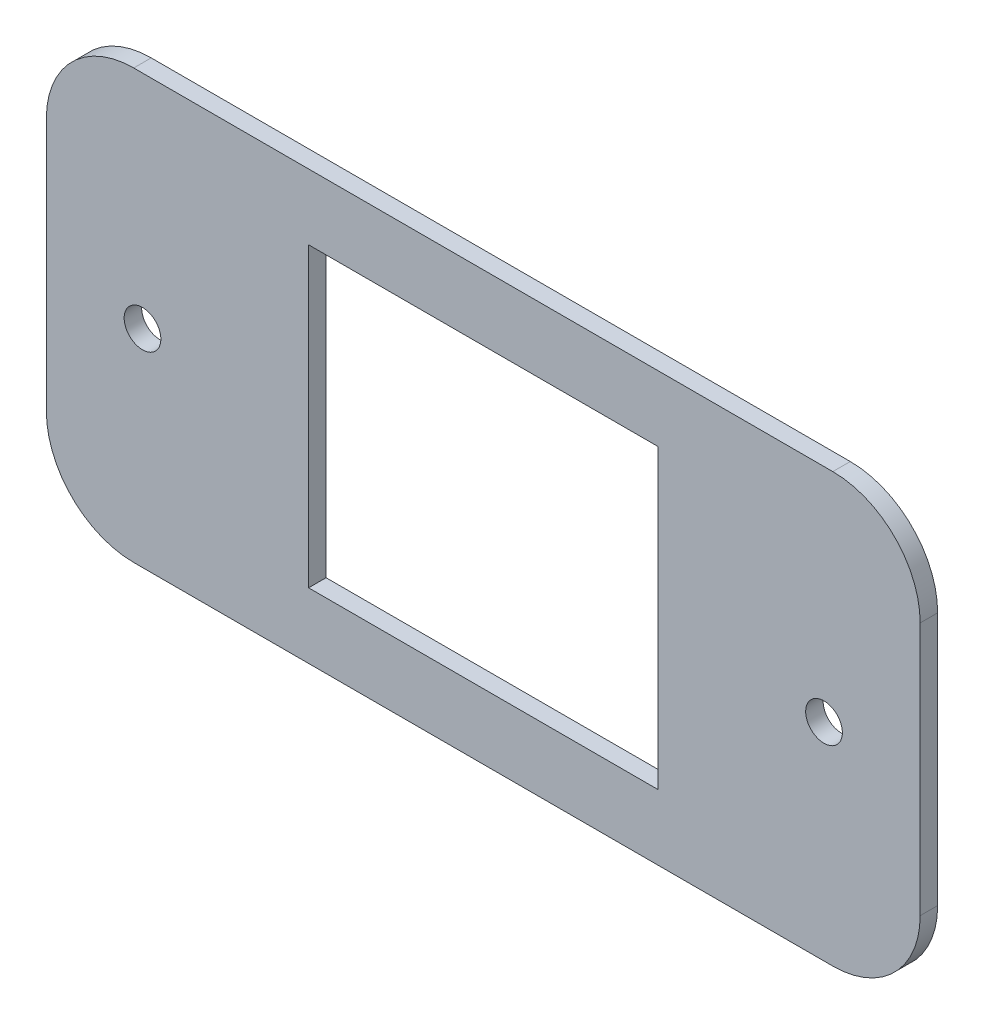
SolidWorks part; units mm, degrees
ref_plane "Front Plane" through (0, 0, 0) normal (0, 0, 1) x (1, 0, 0)
ref_plane "Top Plane" through (0, 0, 0) normal (0, 1, 0) x (1, 0, 0)
ref_plane "Right Plane" through (0, 0, 0) normal (1, 0, 0) x (0, 0, -1)
sketch "Sketch1" plane through (0, 0, 0) normal (0, 0, 1) x (1, 0, 0)
  line L2 (-22.9634, 16.7736) -> (-22.9613, 16.8041)
  line L17 (-22.9613, 16.8041) -> (-23, 16.8041)
  line L19 (13, -13.1959) -> (12.9634, -13.1654) construction
  line L20 (-22.9899, -13.2056) -> (13.0087, -13.2056)
  line L21 (45.0063, -22.7037) -> (-55.0063, -22.7037)
  line L22 (45.0063, -22.7037) -> (45.0063, 26.3119)
  line L23 (45.0063, 26.3119) -> (-55.0063, 26.3119)
  line L24 (-55.0063, -22.7037) -> (-55.0063, 26.3119)
  line L25 (-22.9899, -13.2056) -> (-22.9899, 16.7955)
  line L26 (-22.9899, 16.7955) -> (13.0087, 16.7955)
  line L27 (13.0087, -13.2056) -> (13.0087, 16.7955)
  line L28 (-22.9899, -13.2056) -> (13.0087, 16.7955) construction
  line L29 (-22.9899, 16.7955) -> (13.0087, -13.2056) construction
  line L30 (-22.9634, 16.7736) -> (-23, 16.8041) construction
  line L31 (-24.9899, -15.2056) -> (-24.9899, 18.7955)
  line L32 (-24.9899, 18.7955) -> (15.0087, 18.7955)
  line L33 (15.0087, -15.2056) -> (15.0087, 18.7955)
  line L34 (-24.9899, -15.2056) -> (15.0087, -15.2056)
  circle A0 centre (-44, 0.9817) radius 2.1
  circle A1 centre (34, 0.9817) radius 2.1
  point P0 (0, 0)
  point P1 (-4.9906, 1.7949)
  point P2 (0, 0)
  point P4 (0, 0)
  point P6 (0, 0)
  point P8 (-5, 1.8041)
  point P15 (-5, 1.8041)
  dimension "D1" = 2
extrude "Boss-Extrude1" add sketch "Sketch1" along normal blind 2
fillet "Fillet1" radius 10 4 edges at (-55.0063, -22.7037, 1) (-55.0063, 26.3119, 1) (45.0063, 26.3119, 1) (45.0063, -22.7037, 1)
